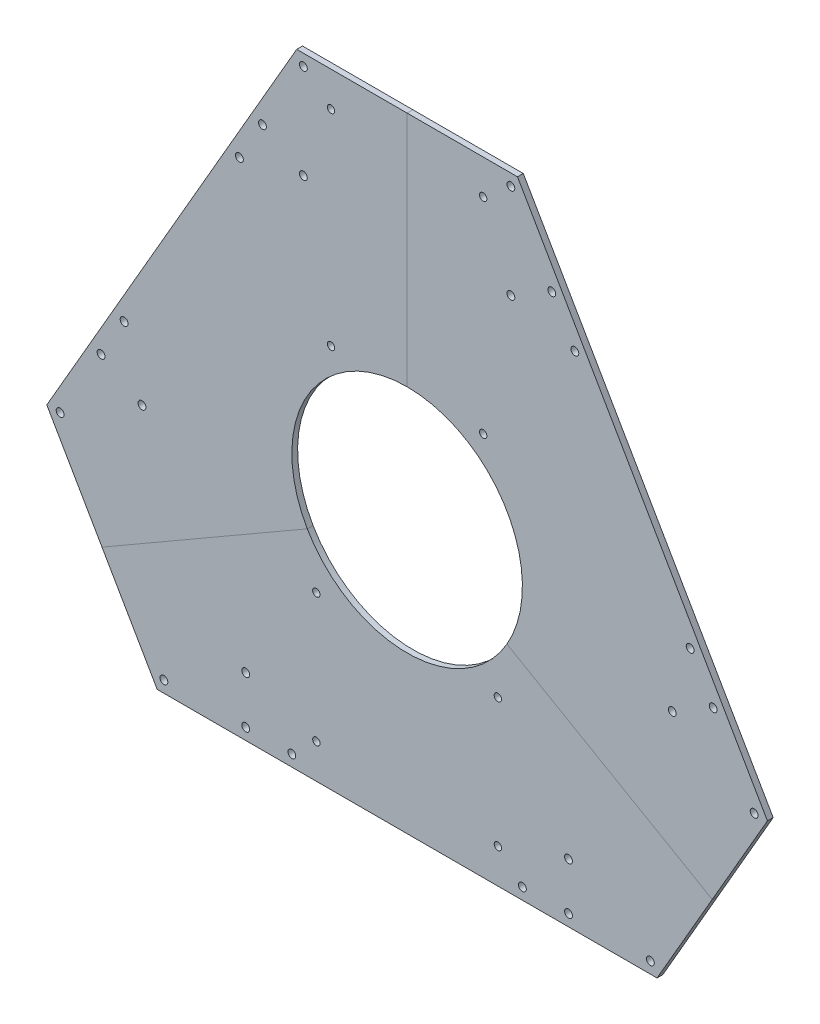
SolidWorks part; units mm, degrees
ref_plane "正面" through (0, 0, 0) normal (0, 0, 1) x (1, 0, 0)
ref_plane "平面" through (0, 0, 0) normal (0, 1, 0) x (1, 0, 0)
ref_plane "右側面" through (0, 0, 0) normal (1, 0, 0) x (0, 0, -1)
sketch "ｽｹｯﾁ1" plane through (0, 0, 0) normal (0, 0, 1) x (1, 0, 0)
  line L0 (0, 0) -> (39.8084, 0)
  line L1 (0, 0) -> (97.7535, 56.438)
  line L2 (132.7535, -4.1838) -> (62.7535, 117.0598)
  line L3 (45, 106.8098) -> (45, 147.8098)
  line L4 (62.7535, 117.0598) -> (42.1132, 152.8098)
  line L5 (62.7535, 117.0598) -> (45, 106.8098)
  line L6 (47.8868, 152.8098) -> (156.2805, -34.9338)
  line L7 (47.8868, 152.8098) -> (-47.8868, 152.8098)
  line L8 (0, 152.8098) -> (0, 0)
  line L9 (132.7535, -4.1838) -> (153.3938, -39.9338)
  line L10 (132.7535, -4.1838) -> (115, -14.4338)
  line L11 (115, -14.4338) -> (150.507, -34.9338)
  line L12 (153.3938, -39.9338) -> (132.3372, -76.4049)
  line L13 (0, 0) -> (132.3372, -76.4049)
  line L14 (153.3938, -39.9338) -> (156.2805, -34.9338)
  circle A0 centre (62.7535, 117.0598) radius 1.7
  circle A1 centre (45, 147.8098) radius 1.7
  circle A2 centre (45, 106.8098) radius 1.7
  circle A3 centre (132.7535, -4.1838) radius 1.7
  circle A4 centre (115, -14.4338) radius 1.7
  circle A5 centre (150.507, -34.9338) radius 1.7
  circle A6 centre (122.7535, 13.1368) radius 1.7
  circle A7 centre (72.7535, 99.7393) radius 1.7
  circle A8 centre (0, 0) radius 50
  point P24 (97.7535, 56.438)
  dimension "D4" = 5
  dimension "D5" = 5
  dimension "D10" = 0
  dimension "D12" = 20
  dimension "D13" = 20
  dimension "D15" = 5
  dimension "D1" = 30
  dimension "D2" = 140
  dimension "D3" = 41
  dimension "D6" = 45
  dimension "D7" = 180
  dimension "D8" = 90
  dimension "D9" = 41
  dimension "D11" = 150
  dimension "D14" = 120
extrude "ﾎﾞｽ - 押し出し1" add sketch "ｽｹｯﾁ1" along normal blind 2.5
pattern_circular "円形ﾊﾟﾀｰﾝ1" count 3 every 120 about axis through (0, 0, 0) along (0, 0, 1) of bodies 101
sketch "ｽｹｯﾁ2" plane through (0, 0, 2.5) normal (0, 0, 1) x (1, 0, 0)
  line L0 (0, -117.876) -> (0, -102.876)
  line L1 (108.3938, -117.876) -> (-108.3938, -117.876) construction
  circle A0 centre (39.37, -102.876) radius 1.6
  circle A1 centre (-39.37, -102.876) radius 1.6
  circle A2 centre (-39.37, -46.996) radius 1.6
  circle A3 centre (39.37, -46.996) radius 1.6
  point P13 (0, 0)
  point P24 (0, 0)
  dimension "D1" = 39.37
  dimension "D2" = 39.37
  dimension "D3" = 55.88
extrude "ｶｯﾄ - 押し出し1" cut sketch "ｽｹｯﾁ2" against normal through all
sketch "ｽｹｯﾁ3" plane through (0, 0, 2.5) normal (0, 0, 1) x (1, 0, 0)
  line L0 (0, 137.8098) -> (33, 137.8098)
  line L1 (0, 152.8098) -> (0, 50) construction
  line L2 (47.8868, 152.8098) -> (0, 152.8098) construction
  circle A0 centre (33, 137.8098) radius 1.6
  circle A1 centre (33, 48.8098) radius 1.6
  dimension "D3" = 89
  dimension "D1" = 33
  dimension "D2" = 15
extrude "ｶｯﾄ - 押し出し2" cut sketch "ｽｹｯﾁ3" against normal through all
sketch "ｽｹｯﾁ4" plane through (0, 0, 2.5) normal (0, 0, 1) x (1, 0, 0)
  line L0 (0, 152.8098) -> (-47.8868, 152.8098) construction
  line L1 (0, 152.8098) -> (0, 50) construction
  circle A0 centre (-33, 137.8098) radius 1.6
  circle A1 centre (-33, 48.8098) radius 1.6
  dimension "D1" = 15
  dimension "D2" = 33
  dimension "D3" = 89
extrude "ｶｯﾄ - 押し出し3" cut sketch "ｽｹｯﾁ4" against normal through all
